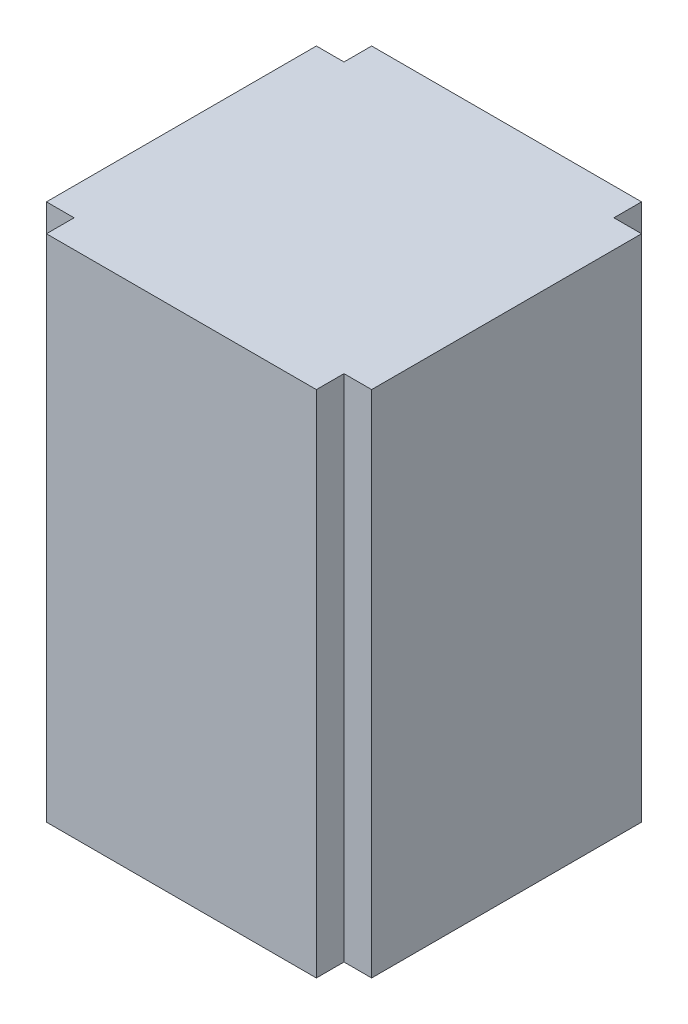
SolidWorks part; units mm, degrees
material "ABS"
ref_plane "Front Plane" through (0, 0, 0) normal (0, 0, 1) x (1, 0, 0)
ref_plane "Top Plane" through (0, 0, 0) normal (0, 1, 0) x (1, 0, 0)
ref_plane "Right Plane" through (0, 0, 0) normal (1, 0, 0) x (0, 0, -1)
sketch "Sketch1" plane through (0, 0, 0) normal (0, 1, 0) x (1, 0, 0)
  line L7 (-34.9152, 45.0525) -> (-34.9152, 53.5525)
  line L8 (48.0848, 45.0525) -> (48.0848, 53.5525)
  line L9 (-34.9152, 53.5525) -> (48.0848, 53.5525)
  line L11 (48.0848, 45.0525) -> (56.5848, 45.0525)
  line L12 (48.0848, -37.9475) -> (56.5848, -37.9475)
  line L13 (56.5848, 45.0525) -> (56.5848, -37.9475)
  line L15 (-34.9152, -37.9475) -> (-34.9152, -46.4475)
  line L16 (48.0848, -37.9475) -> (48.0848, -46.4475)
  line L17 (-34.9152, -46.4475) -> (48.0848, -46.4475)
  line L19 (-34.9152, -37.9475) -> (-43.4152, -37.9475)
  line L20 (-34.9152, 45.0525) -> (-43.4152, 45.0525)
  line L21 (-43.4152, -37.9475) -> (-43.4152, 45.0525)
  point P0 (0, 0)
  dimension "D1" = 100
  dimension "D2" = 100
  dimension "D3" = 8.5
extrude "Boss-Extrude1" add sketch "Sketch1" along normal mid plane 156.7 contours L9 L8 L11 L13 L12 L16 L17 L15 L19 L21 L20 L7
